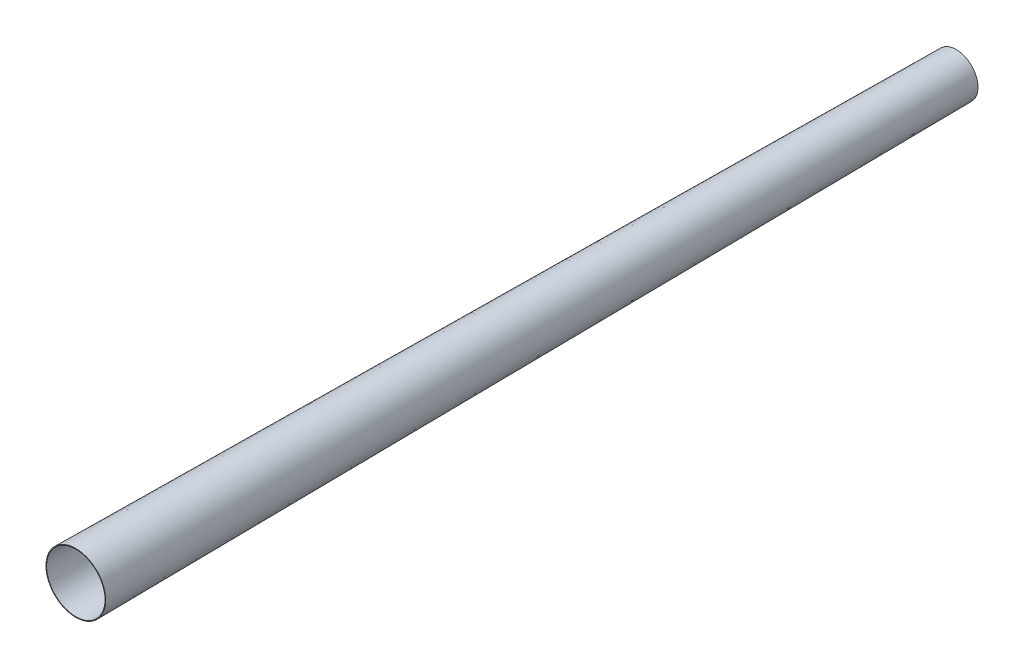
SolidWorks part; units mm, degrees
ref_plane "Front Plane" through (0, 0, 0) normal (0, 0, 1) x (1, 0, 0)
ref_plane "Top Plane" through (0, 0, 0) normal (0, 1, 0) x (1, 0, 0)
ref_plane "Right Plane" through (0, 0, 0) normal (1, 0, 0) x (0, 0, -1)
sketch "Sketch1" plane through (0, 0, 0) normal (0, 0, 1) x (1, 0, 0)
  circle A0 centre (0, 0) radius 16.8661
  circle A1 centre (0, 0) radius 17.3661
  dimension "D2" = 34.7323
  dimension "D1" = 0.5
ref_plane "Plane1" through (0, 0, 700.9946) normal (0, 0, 1) x (1, 0, 0)
sketch "Sketch2" plane through (0, 0, 700.9946) normal (0, 0, 1) x (1, 0, 0)
  circle A0 centre (0, 0) radius 23.7751
  circle A1 centre (0, 0) radius 23.2751
  dimension "D2" = 47.5501
  dimension "D1" = 0.5
loft "Loft1" add section "Sketch1" section "Sketch2"
shell "Shell1" thickness 0.5
